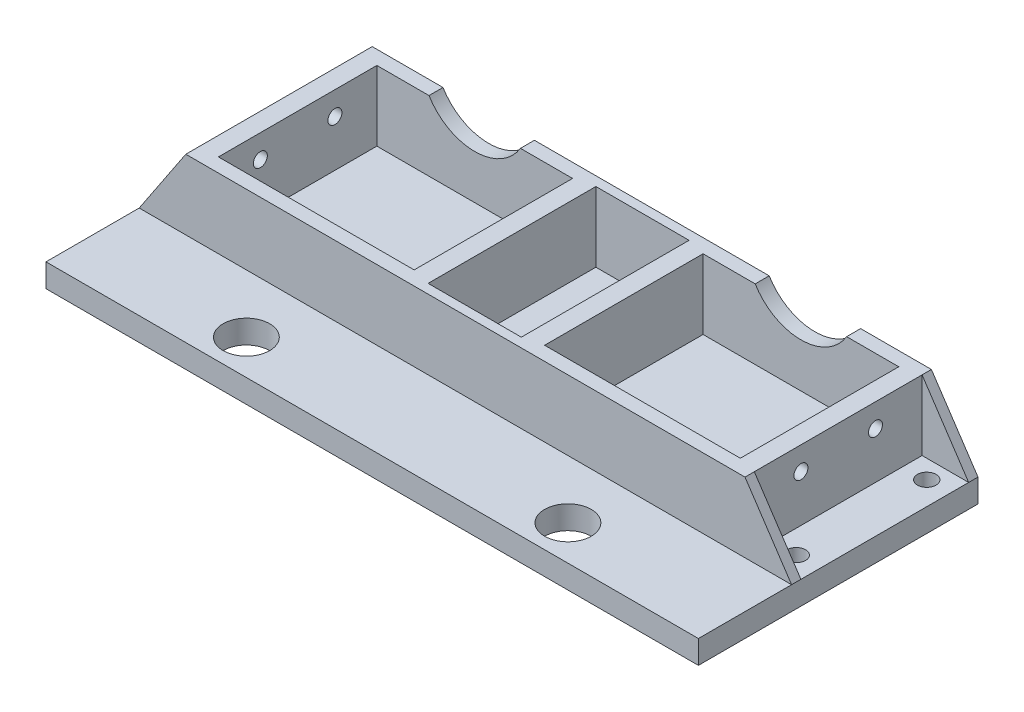
SolidWorks part; units mm, degrees
ref_plane "Front Plane" through (0, 0, 0) normal (0, 0, 1) x (1, 0, 0)
ref_plane "Top Plane" through (0, 0, 0) normal (0, 1, 0) x (1, 0, 0)
ref_plane "Right Plane" through (0, 0, 0) normal (1, 0, 0) x (0, 0, -1)
sketch "Sketch1" plane through (0, 0, 0) normal (0, 1, 0) x (1, 0, 0)
  line L1 (70, -20) -> (-70, -20)
  line L2 (70, -20) -> (70, 20)
  line L3 (70, 20) -> (-70, 20)
  line L4 (-70, -20) -> (-70, 20)
  line L5 (70, -20) -> (-70, 20) construction
  line L6 (70, 20) -> (-70, -20) construction
  point P0 (0, 0)
  dimension "D1" = 140
  dimension "D2" = 40
extrude "Boss-Extrude1" add sketch "Sketch1" along normal blind 20
sketch "Sketch2" plane through (0, 20, 0) normal (0, 1, 0) x (1, 0, 0)
  line L0 (-70, -20) -> (70, -20) construction
  line L1 (-70, 20) -> (-60, 20)
  line L2 (-70, 20) -> (-70, -20)
  line L3 (-70, -20) -> (-60, -20)
  line L4 (-60, 20) -> (-60, -20)
  line L5 (70, 20) -> (-70, 20) construction
  line L6 (70, 20) -> (60, 20)
  line L7 (70, 20) -> (70, -20)
  line L8 (70, -20) -> (60, -20)
  line L9 (60, 20) -> (60, -20)
  line L10 (10, -20) -> (-10, -20)
  line L11 (10, -20) -> (10, 20)
  line L12 (10, 20) -> (-10, 20)
  line L13 (-10, -20) -> (-10, 20)
  line L14 (10, -20) -> (-10, 20) construction
  line L15 (10, 20) -> (-10, -20) construction
  line L17 (-56, 17) -> (-14, 17)
  line L18 (-56, 17) -> (-56, -17)
  line L19 (-56, -17) -> (-14, -17)
  line L20 (-14, 17) -> (-14, -17)
  line L21 (-56, 17) -> (-14, -17) construction
  line L22 (-56, -17) -> (-14, 17) construction
  line L23 (14, -17) -> (56, -17)
  line L24 (14, -17) -> (14, 17)
  line L25 (14, 17) -> (56, 17)
  line L26 (56, -17) -> (56, 17)
  line L27 (14, -17) -> (56, 17) construction
  line L28 (14, 17) -> (56, -17) construction
  point P12 (0, 0)
  point P20 (-35, 0)
  point P25 (35, 0)
  dimension "D1" = 10
  dimension "D2" = 10
  dimension "D3" = 4
  dimension "D4" = 4
  dimension "D5" = 4
  dimension "D6" = 4
  dimension "D7" = 42
  dimension "D8" = 34
extrude "Cut-Extrude1" cut sketch "Sketch2" against normal blind 15
sketch "Sketch3" plane through (-60, 0, 0) normal (-1, 0, 0) x (0, 0, 1)
  line L0 (20, 20) -> (-20, 20) construction
  line L1 (-20, 5) -> (-20, 20) construction
  line L2 (20, 5) -> (20, 20) construction
  circle A0 centre (-8, 15) radius 1.5
  circle A1 centre (8, 15) radius 1.5
  dimension "D1" = 3
  dimension "D5" = 3
  dimension "D2" = 5
  dimension "D3" = 12
  dimension "D4" = 12
extrude "Cut-Extrude2" cut sketch "Sketch3" against normal blind 15
sketch "Sketch4" plane through (0, 0, -20) normal (0, 0, -1) x (-1, 0, 0)
  line L0 (10, 5) -> (60, 5) construction
  line L1 (35, 5) -> (35, 26) construction
  line L2 (0, 55) -> (0, -55) construction
  line L3 (-35, 5) -> (-35, 26) construction
  line L4 (-10, 5) -> (-60, 5) construction
  circle A0 centre (35, 26) radius 11.5
  circle A1 centre (-35, 26) radius 11.5
  dimension "D1" = 23
  dimension "D2" = 21
extrude "Cut-Extrude3" cut sketch "Sketch4" against normal up to surface (3 mm away) up to face at (35, 12.5, -17)
sketch "Sketch5" plane through (0, 5, 0) normal (0, 1, 0) x (1, 0, 0)
  line L0 (-60, 20) -> (-70, 20) construction
  line L1 (-70, -20) -> (-60, -20) construction
  line L2 (-70, 20) -> (-70, -20) construction
  circle A0 centre (-65, 14) radius 2
  circle A1 centre (-65, -14) radius 2
  dimension "D1" = 4
  dimension "D2" = 6
  dimension "D4" = 4
  dimension "D5" = 5
  dimension "D6" = 5
  dimension "D3" = 6
extrude "Cut-Extrude4" cut sketch "Sketch5" against normal up to surface (5 mm away) up to face at (0, 0, 0)
mirror "Mirror1" about plane through (0, 0, 0) normal (1, 0, 0) of "Cut-Extrude4", "Cut-Extrude2"
sketch "Sketch6" plane through (0, 0, 20) normal (0, 0, 1) x (1, 0, 0)
  line L1 (-70, 5) -> (70, 5)
  line L2 (-70, 5) -> (-70, 0)
  line L3 (-70, 0) -> (70, 0)
  line L4 (70, 5) -> (70, 0)
extrude "Boss-Extrude2" add sketch "Sketch6" along normal blind 20
sketch "Sketch7" plane through (0, 5, 0) normal (0, 1, 0) x (1, 0, 0)
  line L0 (-70, -32.5) -> (70, -32.5) construction
  line L1 (-70, 20) -> (-70, -40) construction
  line L2 (70, -40) -> (70, 20) construction
  line L3 (70, -40) -> (-70, -40) construction
  line L4 (0, -11) -> (0, 11) construction
  line L5 (83.5, -40) -> (-83.5, -40) construction
  circle A0 centre (-34.5, -32.5) radius 5
  circle A1 centre (34.5, -32.5) radius 5
  point P18 (0, -40)
  dimension "D2" = 10
  dimension "D1" = 7.5
  dimension "D3" = 34.5
  dimension "D4" = 167
extrude "Cut-Extrude5" cut sketch "Sketch7" against normal up to surface (5 mm away) up to face at (65, 0, -12)
sketch "Sketch8" plane through (0, 0, 20) normal (0, 0, 1) x (1, 0, 0)
  line L0 (-60, 20) -> (-70, 5)
  line L1 (-70, 5) -> (-60, 5)
  line L2 (-60, 5) -> (-60, 20)
  line L4 (-10, 20) -> (10, 20)
  line L5 (-10, 20) -> (-10, 5)
  line L6 (-10, 5) -> (10, 5)
  line L7 (10, 20) -> (10, 5)
extrude "Boss-Extrude3" add sketch "Sketch8" against normal blind 2
pattern_linear "LPattern1" count 2 spacing 38 along (0, 0, -1) of "Boss-Extrude3"
mirror "Mirror2" about plane through (0, 0, 0) normal (1, 0, 0) of "LPattern1", "Boss-Extrude3"
